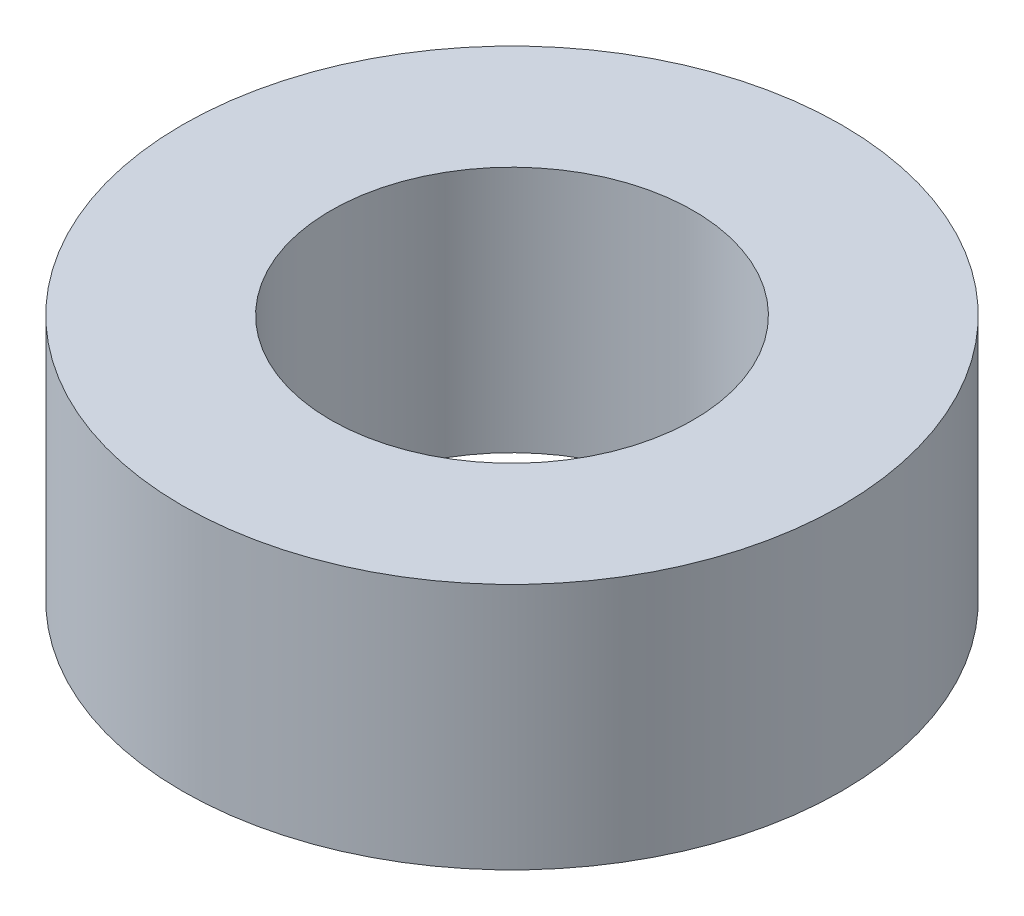
SolidWorks part; units mm, degrees
ref_plane "Front Plane" through (0, 0, 0) normal (0, 0, 1) x (1, 0, 0)
ref_plane "Top Plane" through (0, 0, 0) normal (0, 1, 0) x (1, 0, 0)
ref_plane "Right Plane" through (0, 0, 0) normal (1, 0, 0) x (0, 0, -1)
sketch "Sketch1" plane through (0, 0, 0) normal (0, 1, 0) x (1, 0, 0)
  circle A0 centre (0, 0) radius 1.1
  circle A1 centre (0, 0) radius 2
  dimension "D1" = 2.2
  dimension "D2" = 4
extrude "Boss-Extrude1" add sketch "Sketch1" along normal mid plane 1.5
